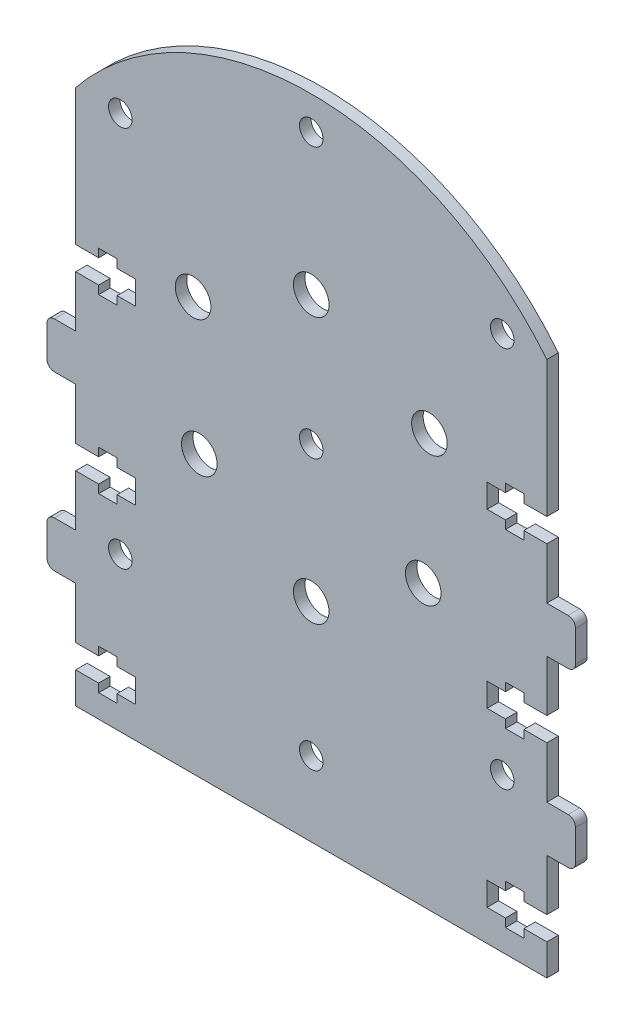
SolidWorks part; units mm, degrees
ref_plane "前视基准面" through (0, 0, 0) normal (0, 0, 1) x (1, 0, 0)
ref_plane "上视基准面" through (0, 0, 0) normal (0, 1, 0) x (1, 0, 0)
ref_plane "右视基准面" through (0, 0, 0) normal (1, 0, 0) x (0, 0, -1)
sketch "草图1" plane through (0, 0, 0) normal (0, 0, 1) x (1, 0, 0)
  line L0 (-14.9625, -1.5035) -> (21.2348, -1.5035) construction
  line L1 (-14.9625, -1.5035) -> (24.3099, -24.1774) construction
  line L2 (-14.9625, -25.2535) -> (-14.9625, -1.5035) construction
  line L3 (26.0375, -61.5035) -> (-55.9625, -61.5035)
  line L4 (26.0375, -61.5035) -> (26.0375, 58.4965) construction
  line L5 (26.0375, 58.4965) -> (-55.9625, 58.4965) construction
  line L7 (26.0375, -61.5035) -> (-55.9625, 58.4965) construction
  line L8 (26.0375, 58.4965) -> (-55.9625, -61.5035) construction
  line L9 (-14.9625, -1.5035) -> (-98.8628, 46.9364) construction
  line L10 (-14.9625, -1.5035) -> (68.9378, 46.9364) construction
  line L11 (-58.2638, 23.4965) -> (-55.9625, 23.4965) construction
  line L12 (-55.9625, 23.4965) -> (-55.9625, 8.0465)
  line L13 (-55.9625, 8.0465) -> (-51.9625, 8.0465)
  line L14 (-51.9625, 8.0465) -> (-51.9625, 9.4965)
  line L15 (-51.9625, 9.4965) -> (-48.7625, 9.4965)
  line L16 (-48.7625, 9.4965) -> (-48.7625, 8.0465)
  line L17 (-48.7625, 8.0465) -> (-45.5625, 8.0465)
  line L18 (-45.5625, 8.0465) -> (-45.5625, 3.9465)
  line L19 (-45.5625, 3.9465) -> (-48.7625, 3.9465)
  line L20 (-48.7625, 3.9465) -> (-48.7625, 2.4965)
  line L21 (-48.7625, 2.4965) -> (-51.9625, 2.4965)
  line L22 (-51.9625, 2.4965) -> (-51.9625, 3.9465)
  line L23 (-51.9625, 3.9465) -> (-55.9625, 3.9465)
  line L24 (-55.9625, -5.0035) -> (-60.9625, -5.0035)
  line L25 (-60.9625, -5.0035) -> (-60.9625, -13.0035)
  line L26 (-60.9625, -13.0035) -> (-55.9625, -13.0035)
  line L27 (-60.9625, -9.0035) -> (-58.1553, -9.0035) construction
  line L28 (-51.9625, -21.9535) -> (-55.9625, -21.9535)
  line L29 (-51.9625, -20.5035) -> (-51.9625, -21.9535)
  line L30 (-48.7625, -20.5035) -> (-51.9625, -20.5035)
  line L31 (-48.7625, -21.9535) -> (-48.7625, -20.5035)
  line L32 (-45.5625, -21.9535) -> (-48.7625, -21.9535)
  line L33 (-45.5625, -26.0535) -> (-45.5625, -21.9535)
  line L34 (-48.7625, -26.0535) -> (-45.5625, -26.0535)
  line L35 (-48.7625, -27.5035) -> (-48.7625, -26.0535)
  line L36 (-51.9625, -27.5035) -> (-48.7625, -27.5035)
  line L37 (-51.9625, -26.0535) -> (-51.9625, -27.5035)
  line L38 (-55.9625, -26.0535) -> (-51.9625, -26.0535)
  line L39 (-55.9625, -21.9535) -> (-55.9625, -13.0035)
  line L40 (-45.5625, -24.0035) -> (-48.2625, -24.0035) construction
  line L41 (-55.9625, -43.0035) -> (-60.9625, -43.0035)
  line L42 (-60.9625, -43.0035) -> (-60.9625, -35.0035)
  line L43 (-60.9625, -35.0035) -> (-55.9625, -35.0035)
  line L44 (-60.9625, -39.0035) -> (-57.1747, -39.0035) construction
  line L45 (-45.5625, -54.0035) -> (-48.2625, -54.0035) construction
  line L46 (-55.9625, 3.9465) -> (-55.9625, -5.0035)
  line L47 (-55.9625, -26.0535) -> (-55.9625, -35.0035)
  line L48 (-55.9625, -51.9535) -> (-51.9625, -51.9535)
  line L49 (-51.9625, -51.9535) -> (-51.9625, -50.5035)
  line L50 (-51.9625, -50.5035) -> (-48.7625, -50.5035)
  line L51 (-48.7625, -50.5035) -> (-48.7625, -51.9535)
  line L52 (-48.7625, -51.9535) -> (-45.5625, -51.9535)
  line L53 (-45.5625, -51.9535) -> (-45.5625, -56.0535)
  line L54 (-45.5625, -56.0535) -> (-48.7625, -56.0535)
  line L55 (-48.7625, -56.0535) -> (-48.7625, -57.5035)
  line L56 (-48.7625, -57.5035) -> (-51.9625, -57.5035)
  line L57 (-51.9625, -57.5035) -> (-51.9625, -56.0535)
  line L58 (-51.9625, -56.0535) -> (-55.9625, -56.0535)
  line L59 (-55.9625, -43.0035) -> (-55.9625, -51.9535)
  line L60 (-55.9625, -56.0535) -> (-55.9625, -61.5035)
  line L61 (15.6375, -54.0035) -> (18.3375, -54.0035) construction
  line L62 (31.0375, -39.0035) -> (27.2497, -39.0035) construction
  line L63 (15.6375, -24.0035) -> (18.3375, -24.0035) construction
  line L64 (31.0375, -9.0035) -> (28.2303, -9.0035) construction
  line L65 (26.0375, -43.0035) -> (26.0375, -51.9535)
  line L66 (22.0375, -56.0535) -> (26.0375, -56.0535)
  line L67 (22.0375, -57.5035) -> (22.0375, -56.0535)
  line L68 (18.8375, -57.5035) -> (22.0375, -57.5035)
  line L69 (18.8375, -56.0535) -> (18.8375, -57.5035)
  line L70 (15.6375, -56.0535) -> (18.8375, -56.0535)
  line L71 (15.6375, -51.9535) -> (15.6375, -56.0535)
  line L72 (18.8375, -51.9535) -> (15.6375, -51.9535)
  line L73 (18.8375, -50.5035) -> (18.8375, -51.9535)
  line L74 (22.0375, -50.5035) -> (18.8375, -50.5035)
  line L75 (22.0375, -51.9535) -> (22.0375, -50.5035)
  line L76 (26.0375, -51.9535) -> (22.0375, -51.9535)
  line L77 (26.0375, -26.0535) -> (26.0375, -35.0035)
  line L78 (26.0375, 3.9465) -> (26.0375, -5.0035)
  line L79 (31.0375, -35.0035) -> (26.0375, -35.0035)
  line L80 (31.0375, -43.0035) -> (31.0375, -35.0035)
  line L81 (26.0375, -43.0035) -> (31.0375, -43.0035)
  line L82 (26.0375, -21.9535) -> (26.0375, -13.0035)
  line L83 (26.0375, -26.0535) -> (22.0375, -26.0535)
  line L84 (22.0375, -26.0535) -> (22.0375, -27.5035)
  line L85 (22.0375, -27.5035) -> (18.8375, -27.5035)
  line L86 (18.8375, -27.5035) -> (18.8375, -26.0535)
  line L87 (18.8375, -26.0535) -> (15.6375, -26.0535)
  line L88 (15.6375, -26.0535) -> (15.6375, -21.9535)
  line L89 (15.6375, -21.9535) -> (18.8375, -21.9535)
  line L90 (18.8375, -21.9535) -> (18.8375, -20.5035)
  line L91 (18.8375, -20.5035) -> (22.0375, -20.5035)
  line L92 (22.0375, -20.5035) -> (22.0375, -21.9535)
  line L93 (22.0375, -21.9535) -> (26.0375, -21.9535)
  line L94 (31.0375, -13.0035) -> (26.0375, -13.0035)
  line L95 (31.0375, -5.0035) -> (31.0375, -13.0035)
  line L96 (26.0375, -5.0035) -> (31.0375, -5.0035)
  line L97 (22.0375, 3.9465) -> (26.0375, 3.9465)
  line L98 (22.0375, 2.4965) -> (22.0375, 3.9465)
  line L99 (18.8375, 2.4965) -> (22.0375, 2.4965)
  line L100 (18.8375, 3.9465) -> (18.8375, 2.4965)
  line L101 (15.6375, 3.9465) -> (18.8375, 3.9465)
  line L102 (15.6375, 8.0465) -> (15.6375, 3.9465)
  line L103 (18.8375, 8.0465) -> (15.6375, 8.0465)
  line L104 (18.8375, 9.4965) -> (18.8375, 8.0465)
  line L105 (22.0375, 9.4965) -> (18.8375, 9.4965)
  line L106 (22.0375, 8.0465) -> (22.0375, 9.4965)
  line L107 (26.0375, 8.0465) -> (22.0375, 8.0465)
  line L108 (26.0375, 23.4965) -> (26.0375, 8.0465)
  line L109 (28.3388, 23.4965) -> (26.0375, 23.4965) construction
  line L110 (26.0375, -56.0535) -> (26.0375, -61.5035)
  line L115 (-55.9625, 23.4965) -> (-55.9625, 31.723)
  line L116 (26.0375, 23.4965) -> (26.0375, 31.723)
  line L117 (-45.5625, 5.9965) -> (-55.9625, 5.9965) construction
  line L118 (-67.9625, -65.7919) -> (38.0375, -65.7919) construction
  line L125 (-55.9625, -61.5035) -> (-67.9625, -61.5035) construction
  line L126 (-67.9625, -61.5035) -> (-67.9625, -65.7919) construction
  line L127 (26.0375, -61.5035) -> (38.0375, -61.5035) construction
  line L128 (38.0375, -61.5035) -> (38.0375, -65.7919) construction
  circle A0 centre (-14.9625, -1.5035) radius 23.75 construction
  circle A1 centre (-14.9625, -1.5035) radius 22.5 construction
  circle A2 centre (-14.9625, -25.2535) radius 3.1
  circle A5 centre (4.5231, -12.7535) radius 3.1
  circle A8 centre (-14.9625, -1.5035) radius 2.05
  circle A15 centre (-14.9625, -1.5035) radius 47 construction
  circle A17 centre (-35.5306, 10.3715) radius 3.1
  circle A18 centre (-34.4481, -12.7535) radius 3.1
  circle A19 centre (5.6056, 10.3715) radius 3.1
  circle A20 centre (-14.9625, 20.9965) radius 3.1
  circle A21 centre (32.0375, -1.5035) radius 2.05 construction
  circle A22 centre (18.2715, -34.7375) radius 2.05
  circle A23 centre (-14.9625, -48.5035) radius 2.05
  circle A24 centre (-48.1965, -34.7375) radius 2.05
  circle A25 centre (-61.9625, -1.5035) radius 2.05 construction
  circle A26 centre (-48.1965, 31.7305) radius 2.05
  circle A27 centre (-14.9625, 45.4965) radius 2.05
  circle A28 centre (18.2715, 31.7305) radius 2.05
  circle A31 centre (-14.9625, -1.5035) radius 52.7731 construction
  arc A34 (-55.9625, 31.723) -> (26.0375, 31.723) centre (-14.9625, -1.5035) cw
  point P41 (-54.9625, -9.0035)
  point P135 (25.0375, -9.0035)
  dimension "D1" = 47.5
  dimension "D2" = 45
  dimension "D3" = 6.2
  dimension "D5" = 6.2
  dimension "D18" = 60
  dimension "D19" = 8
  dimension "D20" = 4.1
  dimension "D21" = 94
  dimension "D22" = 12
  dimension "D23" = 12
  dimension "D4" = 30
  dimension "D6" = 82
  dimension "D8" = 120
  dimension "D9" = 4.1
  dimension "D10" = 3.2
  dimension "D11" = 7
  dimension "D12" = 4
  dimension "D13" = 14
  dimension "D14" = 15
  dimension "D15" = 8
  dimension "D16" = 5
  dimension "D17" = 4
  dimension "D7" = 3
extrude "凸台-拉伸2" add sketch "草图1" along normal blind 2
sketch "草图2" plane through (-55.9625, 0, 0) normal (-1, 0, 0) x (0, 0, 1)
  line L0 (1, -56.0535) -> (1, -51.9535)
  line L1 (2, -56.0535) -> (0, -56.0535) construction
  line L2 (2, -51.9535) -> (0, -51.9535) construction
  circle A0 centre (1, -54.0035) radius 2.05
sketch "草图3" plane through (26.0375, 0, 0) normal (1, 0, 0) x (0, 0, -1)
  line L0 (-1, -51.9535) -> (-1, -56.0535)
  line L1 (-2, -51.9535) -> (0, -51.9535) construction
  line L2 (-2, -56.0535) -> (0, -56.0535) construction
  circle A0 centre (-1, -54.0035) radius 2.05
fillet "圆角1" radius 1.3 8 edges at (-60.9625, -5.0035, 1) (-60.9625, -35.0035, 1) (-60.9625, -13.0035, 1) (-60.9625, -43.0035, 1) (31.0375, -43.0035, 1) (31.0375, -35.0035, 1) (31.0375, -5.0035, 1) (31.0375, -13.0035, 1)
